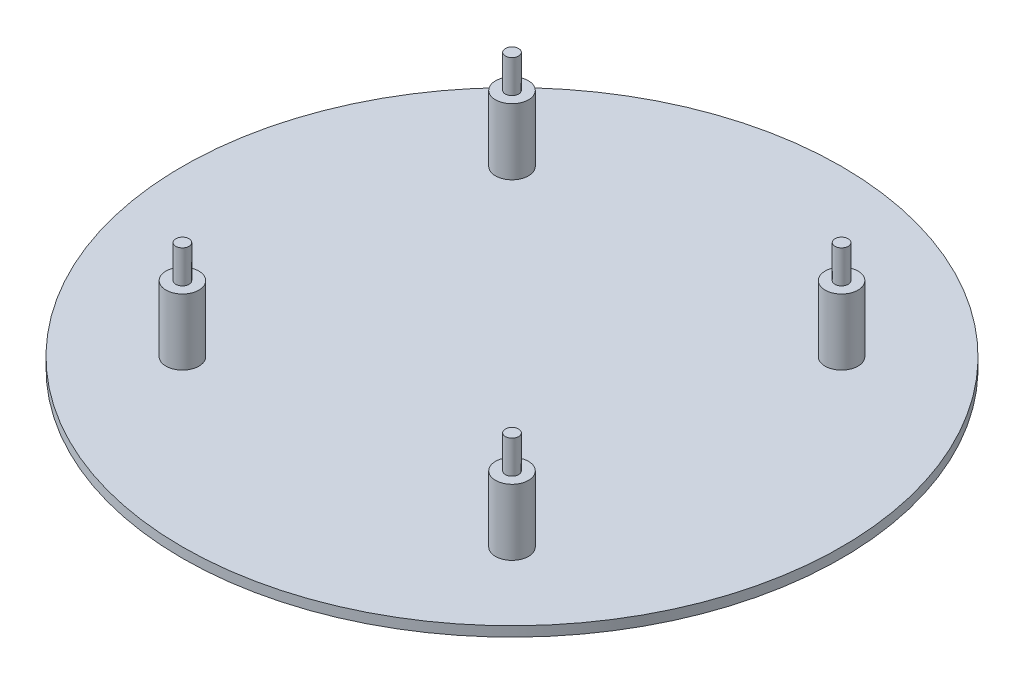
SolidWorks part; units mm, degrees
ref_plane "Front Plane" through (0, 0, 0) normal (0, 0, 1) x (1, 0, 0)
ref_plane "Top Plane" through (0, 0, 0) normal (0, 1, 0) x (1, 0, 0)
ref_plane "Right Plane" through (0, 0, 0) normal (1, 0, 0) x (0, 0, -1)
sketch "Sketch3" plane through (0, 0, 0) normal (0, 1, 0) x (1, 0, 0)
  circle A0 centre (0, 0) radius 100
  dimension "D1" = 200
extrude "Boss-Extrude1" add sketch "Sketch3" along normal blind 3
sketch "Sketch4" plane through (0, 3, 0) normal (0, 1, 0) x (1, 0, 0)
  line L0 (0, -1.65) -> (0, 1.65) construction
  line L1 (-1.65, 0) -> (1.65, 0) construction
  circle A0 centre (-50, 50) radius 5
  circle A1 centre (50, 50) radius 5
  circle A2 centre (50, -50) radius 5
  circle A3 centre (-50, -50) radius 5
  dimension "D3" = 10
  dimension "D1" = 50
  dimension "D2" = 50
  dimension "D4" = 2
  dimension "D5" = 2
extrude "Boss-Extrude2" add sketch "Sketch4" along normal blind 20
sketch "Sketch5" plane through (0, 23, 0) normal (0, 1, 0) x (1, 0, 0)
  circle A0 centre (50, -50) radius 2
  circle A1 centre (-50, -50) radius 2
  circle A2 centre (-50, 50) radius 2
  circle A3 centre (50, 50) radius 2
  dimension "D1" = 4
  dimension "D2" = 2
  dimension "D3" = 2
extrude "Boss-Extrude3" add sketch "Sketch5" along normal blind 10
